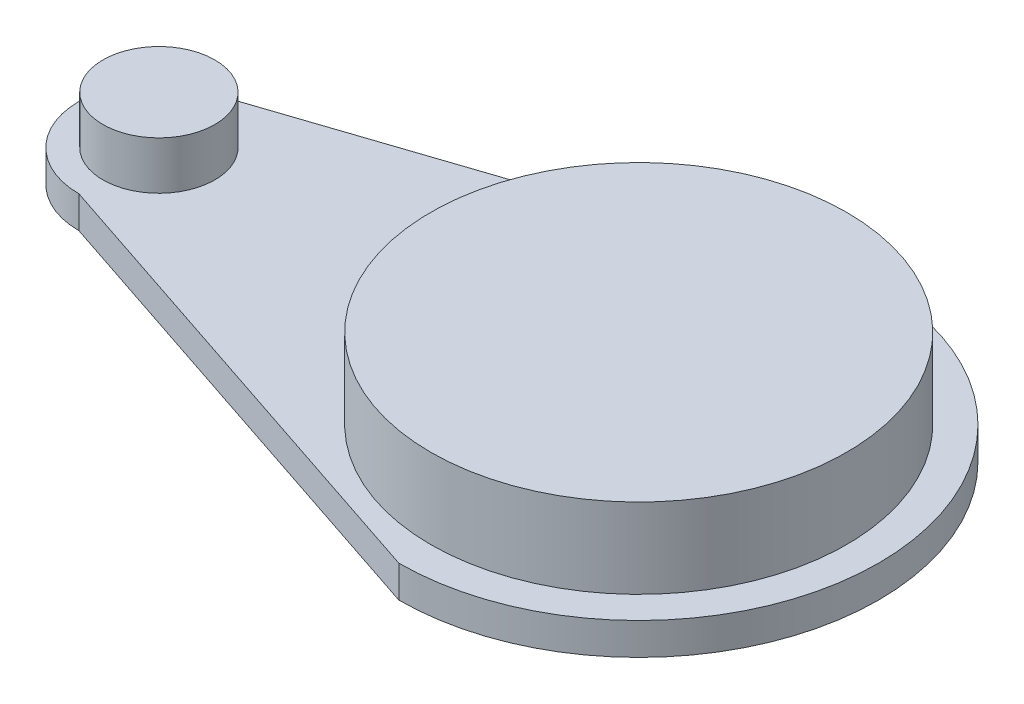
SolidWorks part; units mm, degrees
ref_plane "Front Plane" through (0, 0, 0) normal (0, 0, 1) x (1, 0, 0)
ref_plane "Top Plane" through (0, 0, 0) normal (0, 1, 0) x (1, 0, 0)
ref_plane "Right Plane" through (0, 0, 0) normal (1, 0, 0) x (0, 0, -1)
sketch "Sketch1" plane through (0, 0, 0) normal (0, 1, 0) x (1, 0, 0)
  line L0 (0, 25.4) -> (38.1, 38.1)
  line L1 (0, 0) -> (38.1, 0) construction
  line L2 (0, 0) -> (0, 38.1) construction
  line L3 (0, 38.1) -> (38.1, 38.1) construction
  line L4 (38.1, 0) -> (38.1, 38.1) construction
  line L5 (0, 12.7) -> (38.1, 0)
  arc A0 (38.1, 38.1) -> (38.1, 0) centre (38.1, 19.05) cw
  arc A1 (0, 25.4) -> (0, 12.7) centre (0, 19.05) ccw
  dimension "D3" = 6.35
  dimension "D1" = 38.1
  dimension "D2" = 38.1
extrude "Boss-Extrude1" add sketch "Sketch1" along normal blind 2.54
sketch "Sketch2" plane through (0, 2.54, 0) normal (0, 1, 0) x (1, 0, 0)
  line L0 (38.1, 38.1) -> (38.1, 0) construction
  circle A0 centre (38.1, 19.05) radius 16.51
extrude "Boss-Extrude2" add sketch "Sketch2" along normal blind 6.35
sketch "Sketch3" plane through (0, 2.54, 0) normal (0, 1, 0) x (1, 0, 0)
  line L0 (0, 25.4) -> (0, 12.7) construction
  arc A0 (0, 25.4) -> (0, 12.7) centre (0, 19.05) ccw construction
  circle A1 centre (0, 19.05) radius 4.445
extrude "Boss-Extrude3" add sketch "Sketch3" along normal blind 3.81
ref_plane "Plane1" through (0, 0, -38.1) normal (0, 0, 1) x (1, 0, 0)
ref_plane "MIDPLANE" through (0, 0, -19.05) normal (0, 0, 1) x (1, 0, 0)
